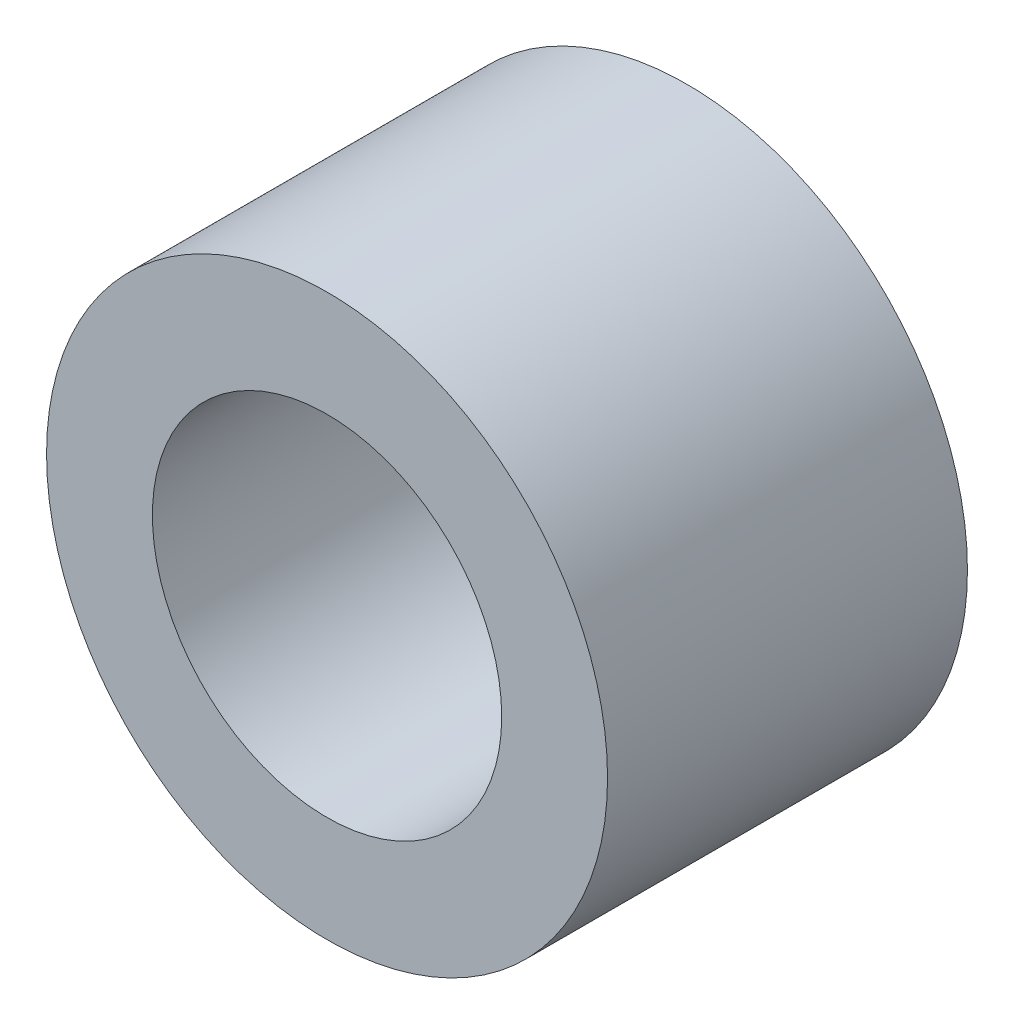
SolidWorks part; units mm, degrees
ref_plane "Спереди" through (0, 0, 0) normal (0, 0, 1) x (1, 0, 0)
ref_plane "Сверху" through (0, 0, 0) normal (0, 1, 0) x (1, 0, 0)
ref_plane "Справа" through (0, 0, 0) normal (1, 0, 0) x (0, 0, -1)
sketch "Эскиз1" plane through (0, 0, 0) normal (0, 0, 1) x (1, 0, 0)
  circle A0 centre (0, 0) radius 1.65
  circle A1 centre (0, 0) radius 2.65
  dimension "D1" = 3.3
  dimension "D2" = 1
extrude "Бобышка-Вытянуть1" add sketch "Эскиз1" along normal blind 3.4
